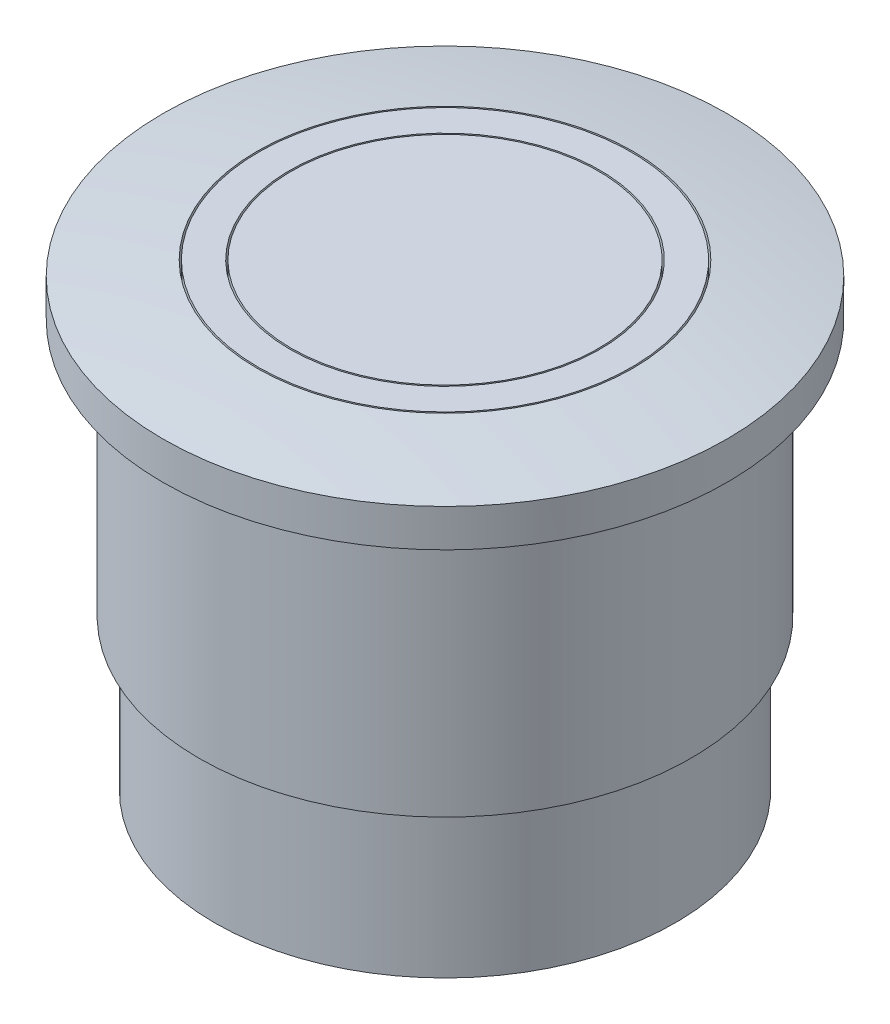
SolidWorks part; units mm, degrees
ref_plane "Front Plane" through (0, 0, 0) normal (0, 0, 1) x (1, 0, 0)
ref_plane "Top Plane" through (0, 0, 0) normal (0, 1, 0) x (1, 0, 0)
ref_plane "Right Plane" through (0, 0, 0) normal (1, 0, 0) x (0, 0, -1)
sketch "Sketch1" plane through (0, 0, 0) normal (0, 1, 0) x (1, 0, 0)
  circle A0 centre (0, 0) radius 7.35
  dimension "D1" = 14.7
extrude "Boss-Extrude1" add sketch "Sketch1" along normal blind 4.8
sketch "Sketch2" plane through (0, 4.8, 0) normal (0, 1, 0) x (1, 0, 0)
  circle A0 centre (0, 0) radius 7.85
  dimension "D1" = 15.7
extrude "Boss-Extrude2" add sketch "Sketch2" along normal offset from surface (8.2 mm away) 13 up to face at (0, 0, 7.35)
sketch "Sketch3" plane through (0, 0, 0) normal (0, 0, 1) x (1, 0, 0)
  line L0 (-7.85, 13) -> (-9, 13)
  line L1 (-9, 13) -> (-9, 14.2)
  line L2 (0, 15.2009) -> (0, -2.1066) construction
  line L5 (7.85, 13) -> (-7.85, 13) construction
  line L6 (0, 13) -> (-7.85, 13)
  line L7 (-6, 14.6554) -> (0, 14.6554)
  line L8 (0, 14.6554) -> (0, 13)
  arc A0 (-6, 14.6554) -> (-9, 14.2) centre (0, -34.9833) ccw
  arc A2 (-49.9694, -33.2333) -> (49.9694, -33.2333) centre (0, -31.4833) ccw
  arc A3 (-49.9694, -33.2333) -> (49.9694, -33.2333) centre (0, -34.9833) ccw
  dimension "D3" = 100
  dimension "D1" = 18
  dimension "D2" = 1.2
  dimension "D4" = 12
revolve "Revolve2" add sketch "Sketch3" angle 360 about L2
sketch "Sketch4" plane through (0, 14.6554, 0) normal (0, 1, 0) x (1, 0, 0)
  line L0 (0, 6) -> (0, 5.95) construction
  line L1 (0, 4.95) -> (0, 4.9) construction
  circle A0 centre (0, 0) radius 5.95
  circle A1 centre (0, 0) radius 6
  circle A2 centre (0, 0) radius 6
  circle A3 centre (0, 0) radius 4.95
  circle A4 centre (0, 0) radius 4.9
  circle M7 centre (0, 0) radius 6
  dimension "D3" = 1
  dimension "D2" = 0.05
  dimension "D1" = 0
extrude "Cut-Extrude1" cut sketch "Sketch4" against normal blind 2 contours A0 M7 | A3 A4
